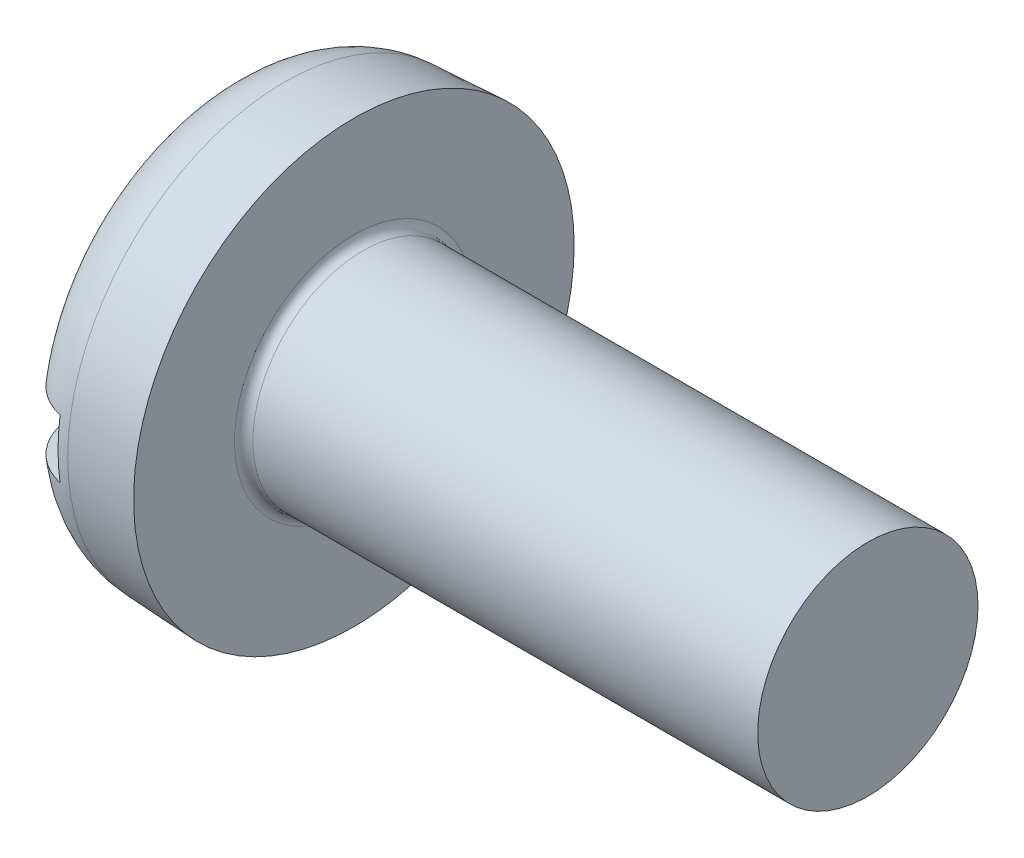
SolidWorks part; units mm, degrees
ref_plane "Front" through (0, 0, 0) normal (0, 0, 1) x (1, 0, 0)
ref_plane "Top" through (0, 0, 0) normal (0, 1, 0) x (1, 0, 0)
ref_plane "Right" through (0, 0, 0) normal (1, 0, 0) x (0, 0, -1)
ref_plane "Plane1" through (3.6, 0, 0) normal (1, 0, 0) x (0, 0, -1)
sketch "Sketch1" plane through (3.6, 0, 0) normal (1, 0, 0) x (0, 0, -1)
  circle A0 centre (0, 0) radius 6
  dimension "dk" = 12
extrude "BaseHead" add sketch "Sketch1" against normal blind 3.6 draft 3
sketch "Sketch2" plane through (3.6, 0, 0) normal (1, 0, 0) x (0, 0, -1)
  line L0 (0, 0) -> (2, 0) construction
  circle A0 centre (0, 0) radius 3
  dimension "d" = 6
  dimension "a" = 2
extrude "BaseBody" add sketch "Sketch2" along normal blind 14
cosmetic thread "ThreadCosmetic1" [suppressed] parameters "D1"=14, "D2"=4.917
fillet "HeadFillet2" radius 1.8 1 edges at (0, 0, -5.8113)
sketch "Sketch3" plane through (1.05, -1.05, 0) normal (0, 0, 1) x (0, -1, 0)
  line L1 (-1.85, 0.35) -> (-0.25, 0.35)
  line L2 (-1.85, 0.35) -> (-1.85, -1.05)
  line L3 (-1.85, -1.05) -> (-0.25, -1.05)
  line L4 (-0.25, 0.35) -> (-0.25, -1.05)
  line L5 (-5.1532, -1.05) -> (3.0532, -1.05) construction
  dimension "n" = 1.6
  dimension "t" = 1.4
  dimension "m" = 0.8
extrude "Notch" cut sketch "Sketch3" against normal through all and the other way through all
fillet "HeadFillet1" radius 0.25 1 edges at (3.6, 0, -3)
sketch "Sketch4" plane through (0, 0, 0) normal (0, 0, 1) x (1, 0, 0)
  line L0 (-20.4, 7.4585) -> (-20.4, 3)
  line L1 (3.6, 7.4585) -> (-20.4, 7.4585)
  line L2 (3.6, 7.4585) -> (3.6, 2.4585)
  line L3 (3.6, 2.4585) -> (-22.9, 2.4585)
  line L6 (6.4188, 0) -> (-0.5067, 0) construction
  line L8 (17.6, -3) -> (17.6, 3) construction
  line L9 (-20.4, 3) -> (-22.9, 2.4585)
  line L11 (3.6, -6) -> (3.6, 6) construction
  line L12 (17.6, 3) -> (3.85, 3) construction
  dimension "dd" = 5
  dimension "b1" = 4.917
  dimension "b" = 38
  dimension "x" = 2.5
sketch "Sketch5" plane through (0, 0, 0) normal (0, 0, 1) x (1, 0, 0)
  line L0 (17.6, 2.531) -> (17.8708, 3)
  line L1 (17.8708, 3) -> (17.8708, 3.5415)
  line L2 (17.8708, 3.5415) -> (17.3293, 3.5415)
  line L3 (17.3293, 3.5415) -> (17.3293, 3)
  line L4 (17.3293, 3) -> (17.6, 2.531)
  line L5 (0, 0) -> (4.296, 0) construction
  line L6 (17.6, -3) -> (17.6, 3) construction
  dimension "D1" = 6
  dimension "D2" = 0.5415
revolve "Cut-Revolve10" [suppressed] cut sketch "Sketch5" angle 360 about L5
pattern_linear "LPattern10" [suppressed] count 22 spacing 0.6498 along (1, 0, 0)
equation "\"m@Sketch3\" = \"n@Sketch3\" / 2"
equation "\"D1@Plane1\" = \"k@BaseHead\""
equation "\"D1@Sketch5\" = \"d@Sketch2\""
equation "\"D2@Sketch5\" =  ( \"d@Sketch2\" - \"D2@ThreadCosmetic1\" )  / 2"
equation "\"D3@LPattern10\" = \"D2@Sketch5\" * 1.2"
equation "\"D1@LPattern10\" = \"D1@ThreadCosmetic1\" / \"D3@LPattern10\" "
